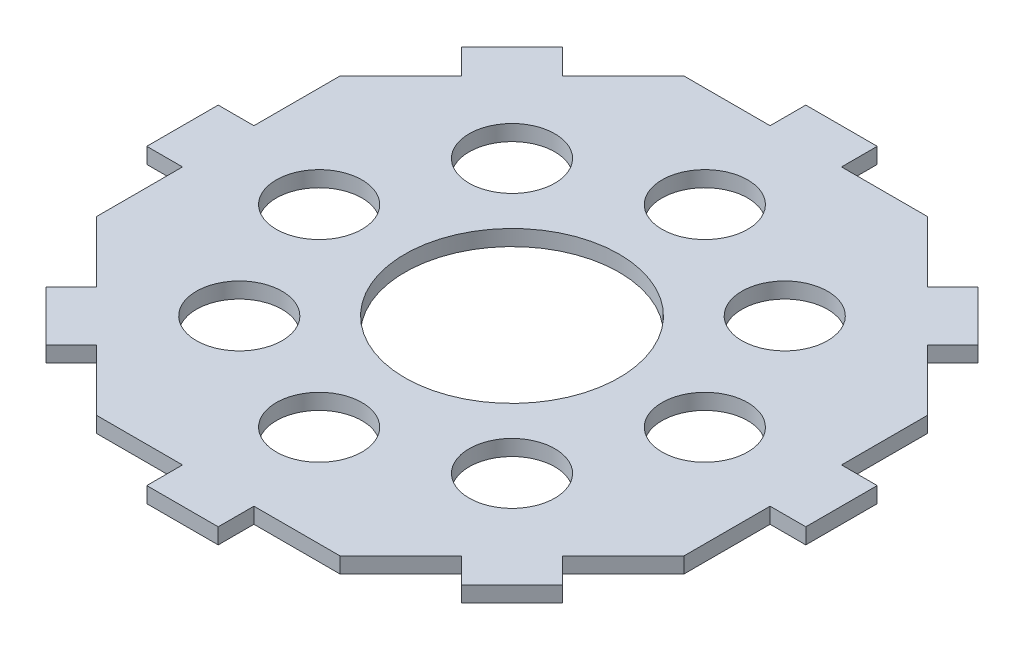
SolidWorks part; units mm, degrees
material "cardboard"
ref_plane "Front Plane" through (0, 0, 0) normal (0, 0, 1) x (1, 0, 0)
ref_plane "Top Plane" through (0, 0, 0) normal (0, 1, 0) x (1, 0, 0)
ref_plane "Right Plane" through (0, 0, 0) normal (1, 0, 0) x (0, 0, -1)
sketch "Sketch1" plane through (0, 0, 0) normal (0, 1, 0) x (1, 0, 0)
  line L0 (-132.1728, 127.1694) -> (-121.1728, 127.1694)
  line L1 (-122.1728, 123.1694) -> (-122.1728, 107.1694)
  line L2 (-62.3728, 123.1694) -> (-62.3728, 107.1694)
  line L3 (-119.7728, 107.1694) -> (-122.1728, 107.1694)
  line L4 (-133.5728, 123.1694) -> (-131.1728, 123.1694)
  line L5 (-133.5728, 123.1694) -> (-133.5728, 107.1694)
  line L6 (-133.5728, 107.1694) -> (-131.1728, 107.1694)
  line L7 (-131.1728, 123.1694) -> (-131.1728, 107.1694)
  line L8 (-119.7728, 123.1694) -> (-119.7728, 107.1694)
  line L9 (-119.7728, 123.1694) -> (-122.1728, 123.1694)
  line L10 (-59.9728, 123.1694) -> (-59.9728, 107.1694)
  line L11 (-96.5728, 127.1694) -> (-85.5728, 127.1694)
  line L12 (-62.3728, 123.1694) -> (-59.9728, 123.1694)
  line L13 (-62.3728, 107.1694) -> (-59.9728, 107.1694)
  line L14 (-50.9728, 123.1694) -> (-50.9728, 107.1694)
  line L15 (-48.5728, 123.1694) -> (-50.9728, 123.1694)
  line L16 (-48.5728, 123.1694) -> (-48.5728, 107.1694)
  line L17 (-48.5728, 107.1694) -> (-50.9728, 107.1694)
  line L18 (8.8272, 123.1694) -> (8.8272, 107.1694)
  line L19 (11.2272, 123.1694) -> (11.2272, 107.1694)
  line L20 (8.8272, 123.1694) -> (11.2272, 123.1694)
  line L21 (8.8272, 107.1694) -> (11.2272, 107.1694)
  line L22 (20.2272, 123.1694) -> (20.2272, 107.1694)
  line L23 (22.6272, 123.1694) -> (20.2272, 123.1694)
  line L24 (22.6272, 123.1694) -> (22.6272, 107.1694)
  line L25 (22.6272, 107.1694) -> (20.2272, 107.1694)
  line L26 (80.0272, 123.1694) -> (80.0272, 107.1694)
  line L27 (82.4272, 123.1694) -> (82.4272, 107.1694)
  line L28 (-60.9728, 127.1694) -> (-49.9728, 127.1694)
  line L29 (80.0272, 123.1694) -> (82.4272, 123.1694)
  line L30 (80.0272, 107.1694) -> (82.4272, 107.1694)
  line L31 (91.4272, 123.1694) -> (91.4272, 107.1694)
  line L32 (56.8272, 129.1694) -> (81.4272, 129.1694)
  line L33 (93.8272, 123.1694) -> (91.4272, 123.1694)
  line L34 (93.8272, 123.1694) -> (93.8272, 107.1694)
  line L35 (93.8272, 107.1694) -> (91.4272, 107.1694)
  line L36 (62.8843, 37.1328) -> (69.3002, 30.717)
  line L37 (82.7871, 17.2301) -> (84.767, 19.2099)
  line L38 (62.8843, 37.1328) -> (64.8642, 39.1127)
  line L39 (76.3712, 23.6459) -> (82.7871, 17.2301)
  line L40 (82.7871, -85.6209) -> (76.3712, -92.0368)
  line L41 (82.7871, -85.6209) -> (84.767, -87.6008)
  line L42 (84.767, -87.6008) -> (64.8642, -107.5036)
  line L43 (62.8843, -105.5237) -> (64.8642, -107.5036)
  line L44 (69.3002, -99.1078) -> (62.8843, -105.5237)
  line L45 (-39.9666, -105.5237) -> (-46.3825, -99.1078)
  line L46 (-39.9666, -105.5237) -> (-41.9465, -107.5036)
  line L47 (-41.9465, -107.5036) -> (-61.8493, -87.6008)
  line L48 (-59.8694, -85.6209) -> (-61.8493, -87.6008)
  line L49 (-53.4536, -92.0368) -> (-59.8694, -85.6209)
  line L50 (-25.3728, 127.1694) -> (-14.3728, 127.1694)
  line L51 (10.2272, 127.1694) -> (21.2272, 127.1694)
  line L52 (45.8272, 127.1694) -> (56.8272, 127.1694)
  line L53 (81.4272, 127.1694) -> (92.4272, 127.1694)
  line L54 (117.0272, 127.1694) -> (128.0272, 127.1694)
  line L55 (-36.6432, -102.2003) -> (-34.5738, -104.2697)
  line L56 (-6.2376, -76.0373) -> (-4.1682, -78.1068)
  line L57 (-56.546, -82.2975) -> (-58.3138, -84.0653)
  line L58 (-36.6432, -102.2003) -> (-38.411, -103.9681)
  line L59 (-32.4525, -49.8225) -> (-58.6154, -75.9854)
  line L60 (-58.6154, -80.2281) -> (-56.546, -82.2975)
  line L61 (-4.1682, -78.1068) -> (-30.3312, -104.2697)
  line L62 (-32.4525, -49.8225) -> (-30.3831, -51.8919)
  line L63 (-144.4728, 129.1694) -> (-132.1728, 129.1694)
  line L64 (-55.8571, 81.8711) -> (-55.8571, 86.8711)
  line L65 (-65.8571, 81.8711) -> (-65.8571, 86.8711)
  line L66 (-35.3072, 73.3591) -> (-31.7716, 76.8946)
  line L67 (-28.2361, 66.288) -> (-24.7006, 69.8235)
  line L68 (-19.724, 45.7381) -> (-14.724, 45.7381)
  line L69 (-19.724, 35.7381) -> (-14.724, 35.7381)
  line L70 (-28.2361, 15.1882) -> (-24.7006, 11.6526)
  line L71 (-35.3072, 8.1171) -> (-31.7716, 4.5816)
  line L72 (-55.8571, -0.3949) -> (-55.8571, -5.3949)
  line L73 (-65.8571, -0.3949) -> (-65.8571, -5.3949)
  line L74 (-86.407, 8.1171) -> (-89.9425, 4.5816)
  line L75 (61.3287, 35.5772) -> (67.7445, 29.1613)
  line L76 (74.8156, 22.0903) -> (81.2315, 15.6744)
  line L77 (74.8156, 22.0903) -> (76.3712, 23.6459)
  line L78 (67.7445, 29.1613) -> (69.3002, 30.717)
  line L79 (29.5322, -77.8285) -> (32.3607, -75)
  line L80 (55.0919, -16.122) -> (52.2634, -13.2936)
  line L81 (-144.4728, 129.1694) -> (-144.4728, 119.1694)
  line L82 (-6.6146, 9.4376) -> (-32.1742, -16.122)
  line L83 (-144.4728, 101.1694) -> (-128.6728, 101.1694)
  line L84 (-93.4781, 15.1882) -> (-97.0136, 11.6526)
  line L85 (-108.8728, 120.1694) -> (-108.8728, 110.1694)
  line L86 (64.8642, 39.1127) -> (84.767, 19.2099)
  line L87 (-22.9584, -48.7099) -> (-3.0557, -68.6127)
  line L88 (-22.9584, -48.7099) -> (-26.1404, -51.8919)
  line L89 (-3.0557, -68.6127) -> (-6.2376, -71.7947)
  line L90 (-32.1742, -16.122) -> (-67.1742, -16.122)
  line L91 (-82.1742, -31.122) -> (-82.1742, -37.2688)
  line L92 (-67.1742, -52.2688) -> (-34.8988, -52.2688)
  line L93 (-112.1728, 106.1694) -> (-114.6728, 106.1694)
  line L94 (-141.1728, 126.1694) -> (-138.6728, 126.1694)
  line L95 (-141.1728, 126.1694) -> (-141.1728, 106.1694)
  line L96 (-141.1728, 106.1694) -> (-138.6728, 106.1694)
  line L97 (-138.6728, 126.1694) -> (-138.6728, 106.1694)
  line L98 (-114.6728, 126.1694) -> (-114.6728, 106.1694)
  line L99 (29.5322, 9.4376) -> (29.5322, 44.4376)
  line L100 (14.5322, 59.4376) -> (8.3854, 59.4376)
  line L101 (-6.6146, 44.4376) -> (-6.6146, 9.4376)
  line L102 (-112.1728, 126.1694) -> (-114.6728, 126.1694)
  line L103 (-112.1728, 126.1694) -> (-112.1728, 106.1694)
  line L104 (-124.6728, 101.1694) -> (-110.3728, 101.1694)
  line L105 (-108.8728, 120.1694) -> (-108.8728, 110.1694)
  line L106 (55.0919, -52.2688) -> (90.0919, -52.2688)
  line L107 (105.0919, -37.2688) -> (105.0919, -31.122)
  line L108 (90.0919, -16.122) -> (55.0919, -16.122)
  line L109 (-74.7728, 101.1694) -> (-73.2728, 101.1694)
  line L110 (-73.2728, 129.1694) -> (-73.2728, 101.1694)
  line L111 (21.2272, 129.1694) -> (45.8272, 129.1694)
  line L112 (-73.2728, 129.1694) -> (-73.2728, 101.1694)
  line L113 (-73.2728, 101.1694) -> (-37.6728, 101.1694)
  line L114 (-37.6728, 129.1694) -> (-37.6728, 101.1694)
  line L115 (-6.6146, -80.5531) -> (-6.6146, -112.8285)
  line L116 (8.3854, -127.8285) -> (14.5322, -127.8285)
  line L117 (29.5322, -112.8285) -> (29.5322, -77.8285)
  line L118 (-14.3728, 129.1694) -> (10.2272, 129.1694)
  line L119 (-37.6728, 129.1694) -> (-37.6728, 101.1694)
  line L120 (-37.6728, 101.1694) -> (-2.0728, 101.1694)
  line L121 (-2.0728, 129.1694) -> (-2.0728, 101.1694)
  line L122 (-49.9728, 129.1694) -> (-25.3728, 129.1694)
  line L123 (-2.0728, 129.1694) -> (-2.0728, 101.1694)
  line L124 (52.2634, -55.0972) -> (55.0919, -52.2688)
  line L125 (25.9733, -68.6127) -> (45.8761, -48.7099)
  line L126 (81.2315, -84.0653) -> (74.8156, -90.4811)
  line L127 (45.8761, -48.7099) -> (81.2315, -84.0653)
  line L128 (74.8156, -90.4811) -> (76.3712, -92.0368)
  line L129 (78.3511, -94.0167) -> (71.2801, -101.0877)
  line L130 (25.9733, -68.6127) -> (61.3287, -103.9681)
  line L131 (67.7445, -97.5522) -> (69.3002, -99.1078)
  line L132 (67.7445, -97.5522) -> (61.3287, -103.9681)
  line L133 (-38.411, -103.9681) -> (-44.8269, -97.5522)
  line L134 (-44.8269, -97.5522) -> (-46.3825, -99.1078)
  line L135 (32.3607, 6.6092) -> (29.5322, 9.4376)
  line L136 (-101.9901, 35.7381) -> (-106.9901, 35.7381)
  line L137 (45.8761, -19.6809) -> (25.9733, 0.2219)
  line L138 (45.8761, -19.6809) -> (81.2315, 15.6744)
  line L139 (25.9733, 0.2219) -> (61.3287, 35.5772)
  line L140 (-48.3624, -101.0877) -> (-55.4335, -94.0167)
  line L141 (-51.8979, -90.4811) -> (-53.4536, -92.0368)
  line L142 (-51.8979, -90.4811) -> (-58.3138, -84.0653)
  line L143 (-65.8571, 81.8711) -> (-77.8949, 81.8711)
  line L144 (-77.8949, 81.8711) -> (-86.407, 73.3591)
  line L145 (-2.0728, 101.1694) -> (33.5272, 101.1694)
  line L146 (33.5272, 129.1694) -> (33.5272, 101.1694)
  line L147 (-85.5728, 129.1694) -> (-60.9728, 129.1694)
  line L148 (33.5272, 129.1694) -> (33.5272, 101.1694)
  line L149 (33.5272, 101.1694) -> (69.1272, 101.1694)
  line L150 (69.1272, 129.1694) -> (69.1272, 101.1694)
  line L151 (-121.1728, 129.1694) -> (-110.3728, 129.1694)
  line L152 (69.1272, 129.1694) -> (69.1272, 101.1694)
  line L153 (69.1272, 101.1694) -> (104.7272, 101.1694)
  line L154 (104.7272, 129.1694) -> (104.7272, 101.1694)
  line L155 (128.0272, 129.1694) -> (140.3272, 129.1694)
  line L156 (104.7272, 129.1694) -> (104.7272, 101.1694)
  line L157 (104.7272, 101.1694) -> (140.3272, 101.1694)
  line L158 (140.3272, 129.1694) -> (140.3272, 119.1694)
  line L159 (-69.9728, 126.1694) -> (-67.4728, 126.1694)
  line L160 (-69.9728, 126.1694) -> (-69.9728, 106.1694)
  line L161 (-69.9728, 106.1694) -> (-67.4728, 106.1694)
  line L162 (-67.4728, 126.1694) -> (-67.4728, 106.1694)
  line L163 (-43.4728, 126.1694) -> (-43.4728, 106.1694)
  line L164 (-40.9728, 106.1694) -> (-43.4728, 106.1694)
  line L165 (-40.9728, 126.1694) -> (-40.9728, 106.1694)
  line L166 (-40.9728, 126.1694) -> (-43.4728, 126.1694)
  line L167 (-61.4728, 101.1694) -> (-61.4728, 97.1694)
  line L168 (-61.4728, 97.1694) -> (-49.4728, 97.1694)
  line L169 (-49.4728, 97.1694) -> (-49.4728, 101.1694)
  line L170 (1.2272, 126.1694) -> (3.7272, 126.1694)
  line L171 (1.2272, 126.1694) -> (1.2272, 106.1694)
  line L172 (1.2272, 106.1694) -> (3.7272, 106.1694)
  line L173 (3.7272, 126.1694) -> (3.7272, 106.1694)
  line L174 (27.7272, 126.1694) -> (27.7272, 106.1694)
  line L175 (30.2272, 106.1694) -> (27.7272, 106.1694)
  line L176 (30.2272, 126.1694) -> (30.2272, 106.1694)
  line L177 (30.2272, 126.1694) -> (27.7272, 126.1694)
  line L178 (9.7272, 101.1694) -> (9.7272, 97.1694)
  line L179 (9.7272, 97.1694) -> (21.7272, 97.1694)
  line L180 (21.7272, 97.1694) -> (21.7272, 101.1694)
  line L181 (72.4272, 126.1694) -> (74.9272, 126.1694)
  line L182 (72.4272, 126.1694) -> (72.4272, 106.1694)
  line L183 (72.4272, 106.1694) -> (74.9272, 106.1694)
  line L184 (74.9272, 126.1694) -> (74.9272, 106.1694)
  line L185 (98.9272, 126.1694) -> (98.9272, 106.1694)
  line L186 (101.4272, 106.1694) -> (98.9272, 106.1694)
  line L187 (101.4272, 126.1694) -> (101.4272, 106.1694)
  line L188 (101.4272, 126.1694) -> (98.9272, 126.1694)
  line L189 (80.9272, 101.1694) -> (80.9272, 97.1694)
  line L190 (80.9272, 97.1694) -> (92.9272, 97.1694)
  line L191 (92.9272, 97.1694) -> (92.9272, 101.1694)
  line L192 (-128.6728, 101.1694) -> (-128.6728, 102.1694)
  line L193 (-128.6728, 102.1694) -> (-124.6728, 102.1694)
  line L194 (-124.6728, 102.1694) -> (-124.6728, 101.1694)
  line L195 (-61.4728, 100.1694) -> (-57.4728, 100.1694)
  line L196 (-57.4728, 100.1694) -> (-57.4728, 102.1694)
  line L197 (-57.4728, 102.1694) -> (-53.4728, 102.1694)
  line L198 (-53.4728, 102.1694) -> (-53.4728, 100.1694)
  line L199 (-53.4728, 100.1694) -> (-49.4728, 100.1694)
  line L200 (9.7272, 100.1694) -> (13.7272, 100.1694)
  line L201 (13.7272, 100.1694) -> (13.7272, 102.1694)
  line L202 (13.7272, 102.1694) -> (17.7272, 102.1694)
  line L203 (27.3876, 1.6361) -> (33.7515, -4.7279)
  line L204 (33.7515, -4.7279) -> (30.9231, -7.5563)
  line L205 (30.9231, -7.5563) -> (38.098, -14.7312)
  line L206 (38.098, -14.7312) -> (40.9264, -11.9027)
  line L207 (40.9264, -11.9027) -> (47.2903, -18.2667)
  line L208 (47.2903, -50.1241) -> (40.9264, -56.4881)
  line L209 (40.9264, -56.4881) -> (38.098, -53.6597)
  line L210 (38.098, -53.6597) -> (30.9231, -60.8345)
  line L211 (30.9231, -60.8345) -> (33.7515, -63.663)
  line L212 (33.7515, -63.663) -> (27.3876, -70.0269)
  line L213 (-4.4699, -70.0269) -> (-10.8338, -63.663)
  line L214 (-10.8338, -63.663) -> (-8.0054, -60.8345)
  line L215 (-8.0054, -60.8345) -> (-15.1803, -53.6597)
  line L216 (-15.1803, -53.6597) -> (-18.0087, -56.4881)
  line L217 (-18.0087, -56.4881) -> (-24.3727, -50.1241)
  line L218 (-89.9425, 76.8946) -> (-97.0136, 69.8235)
  line L219 (-93.4781, 66.288) -> (-101.9901, 57.7759)
  line L220 (-101.9901, 57.7759) -> (-101.9901, 45.7381)
  line L221 (-106.9901, 45.7381) -> (-106.9901, 35.7381)
  line L222 (-101.9901, 35.7381) -> (-101.9901, 23.7002)
  line L223 (-101.9901, 23.7002) -> (-93.4781, 15.1882)
  line L224 (-97.0136, 11.6526) -> (-89.9425, 4.5816)
  line L225 (-86.407, 8.1171) -> (-77.8949, -0.3949)
  line L226 (-77.8949, -0.3949) -> (-65.8571, -0.3949)
  line L227 (-65.8571, -5.3949) -> (-55.8571, -5.3949)
  line L228 (-55.8571, -0.3949) -> (-43.8192, -0.3949)
  line L229 (-43.8192, -0.3949) -> (-35.3072, 8.1171)
  line L230 (-31.7716, 4.5816) -> (-24.7006, 11.6526)
  line L231 (-28.2361, 15.1882) -> (-19.724, 23.7002)
  line L232 (-19.724, 23.7002) -> (-19.724, 35.7381)
  line L233 (-14.724, 35.7381) -> (-14.724, 45.7381)
  line L234 (-19.724, 45.7381) -> (-19.724, 57.7759)
  line L235 (-19.724, 57.7759) -> (-28.2361, 66.288)
  line L236 (-24.7006, 69.8235) -> (-31.7716, 76.8946)
  line L237 (-35.3072, 73.3591) -> (-43.8192, 81.8711)
  line L238 (-43.8192, 81.8711) -> (-55.8571, 81.8711)
  line L239 (-55.8571, 86.8711) -> (-65.8571, 86.8711)
  line L240 (-101.9901, 45.7381) -> (-106.9901, 45.7381)
  line L241 (-93.4781, 66.288) -> (-97.0136, 69.8235)
  line L242 (-86.407, 73.3591) -> (-89.9425, 76.8946)
  line L243 (17.7272, 102.1694) -> (17.7272, 100.1694)
  line L244 (17.7272, 100.1694) -> (21.7272, 100.1694)
  line L245 (80.9272, 100.1694) -> (84.9272, 100.1694)
  line L246 (84.9272, 100.1694) -> (84.9272, 102.1694)
  line L247 (84.9272, 102.1694) -> (88.9272, 102.1694)
  line L248 (88.9272, 102.1694) -> (88.9272, 100.1694)
  line L249 (88.9272, 100.1694) -> (92.9272, 100.1694)
  line L250 (140.3272, 119.1694) -> (142.3272, 119.1694)
  line L251 (142.3272, 111.1694) -> (140.3272, 111.1694)
  line L252 (140.3272, 111.1694) -> (140.3272, 101.1694)
  line L253 (-144.4728, 119.1694) -> (-143.4728, 119.1694)
  line L254 (-143.4728, 119.1694) -> (-143.4728, 111.1694)
  line L255 (-143.4728, 111.1694) -> (-144.4728, 111.1694)
  line L256 (-144.4728, 111.1694) -> (-144.4728, 101.1694)
  line L257 (-110.3728, 129.1694) -> (-110.3728, 120.1694)
  line L258 (-110.3728, 120.1694) -> (-108.8728, 120.1694)
  line L259 (-108.8728, 110.1694) -> (-110.3728, 110.1694)
  line L260 (-110.3728, 110.1694) -> (-110.3728, 101.1694)
  line L261 (-74.7728, 129.1694) -> (-74.7728, 120.1694)
  line L262 (-74.7728, 120.1694) -> (-71.7728, 120.1694)
  line L263 (-71.7728, 120.1694) -> (-71.7728, 110.1694)
  line L264 (-71.7728, 110.1694) -> (-74.7728, 110.1694)
  line L265 (-74.7728, 110.1694) -> (-74.7728, 101.1694)
  line L266 (-39.1728, 129.1694) -> (-39.1728, 120.1694)
  line L267 (-39.1728, 120.1694) -> (-36.1728, 120.1694)
  line L268 (-36.1728, 120.1694) -> (-36.1728, 110.1694)
  line L269 (-36.1728, 110.1694) -> (-39.1728, 110.1694)
  line L270 (-39.1728, 110.1694) -> (-39.1728, 101.1694)
  line L271 (-3.5728, 129.1694) -> (-3.5728, 120.1694)
  line L272 (-3.5728, 120.1694) -> (-0.5728, 120.1694)
  line L273 (-0.5728, 120.1694) -> (-0.5728, 110.1694)
  line L274 (-0.5728, 110.1694) -> (-3.5728, 110.1694)
  line L275 (-3.5728, 110.1694) -> (-3.5728, 101.1694)
  line L276 (32.0272, 129.1694) -> (32.0272, 120.1694)
  line L277 (32.0272, 120.1694) -> (35.0272, 120.1694)
  line L278 (35.0272, 120.1694) -> (35.0272, 110.1694)
  line L279 (35.0272, 110.1694) -> (32.0272, 110.1694)
  line L280 (32.0272, 110.1694) -> (32.0272, 101.1694)
  line L281 (67.6272, 129.1694) -> (67.6272, 120.1694)
  line L282 (67.6272, 120.1694) -> (70.6272, 120.1694)
  line L283 (70.6272, 120.1694) -> (70.6272, 110.1694)
  line L284 (70.6272, 110.1694) -> (67.6272, 110.1694)
  line L285 (67.6272, 110.1694) -> (67.6272, 101.1694)
  line L286 (103.2272, 129.1694) -> (103.2272, 120.1694)
  line L287 (103.2272, 120.1694) -> (106.2272, 120.1694)
  line L288 (106.2272, 120.1694) -> (106.2272, 110.1694)
  line L289 (106.2272, 110.1694) -> (103.2272, 110.1694)
  line L290 (103.2272, 110.1694) -> (103.2272, 101.1694)
  line L291 (142.3272, 119.1694) -> (142.3272, 111.1694)
  line L292 (-132.1728, 129.1694) -> (-132.1728, 127.1694)
  line L293 (-121.1728, 129.1694) -> (-121.1728, 127.1694)
  line L294 (-96.5728, 129.1694) -> (-96.5728, 127.1694)
  line L295 (-85.5728, 129.1694) -> (-85.5728, 127.1694)
  line L296 (-60.9728, 129.1694) -> (-60.9728, 127.1694)
  line L297 (-49.9728, 129.1694) -> (-49.9728, 127.1694)
  line L298 (-25.3728, 129.1694) -> (-25.3728, 127.1694)
  line L299 (-14.3728, 129.1694) -> (-14.3728, 127.1694)
  line L300 (10.2272, 129.1694) -> (10.2272, 127.1694)
  line L301 (21.2272, 129.1694) -> (21.2272, 127.1694)
  line L302 (45.8272, 129.1694) -> (45.8272, 127.1694)
  line L303 (56.8272, 129.1694) -> (56.8272, 127.1694)
  line L304 (81.4272, 129.1694) -> (81.4272, 127.1694)
  line L305 (92.4272, 129.1694) -> (92.4272, 127.1694)
  line L306 (117.0272, 129.1694) -> (117.0272, 127.1694)
  line L307 (128.0272, 129.1694) -> (128.0272, 127.1694)
  line L308 (92.4272, 129.1694) -> (117.0272, 129.1694)
  circle A0 centre (-32.4525, -56.8936) radius 1.75
  circle A1 centre (-60.8571, 67.7381) radius 6
  circle A2 centre (-41.7652, 59.83) radius 6
  circle A3 centre (-33.8571, 40.7381) radius 6
  circle A4 centre (-11.2393, -78.1068) radius 1.75
  circle A5 centre (-32.4525, -99.32) radius 1.75
  circle A6 centre (11.4588, 34.4376) radius 10
  circle A7 centre (-126.6728, 113.6694) radius 1
  circle A8 centre (-53.6657, -78.1068) radius 1.75
  arc A9 (-30.3831, -51.8919) -> (-26.1404, -51.8919) centre (-28.2617, -49.7706) ccw
  arc A10 (-6.2376, -76.0373) -> (-6.2376, -71.7947) centre (-4.1163, -73.916) cw
  circle A11 centre (-55.4728, 113.6694) radius 1
  circle A12 centre (80.0919, -34.1954) radius 10
  circle A13 centre (11.4588, -34.1954) radius 15
  arc A14 (-67.1742, -16.122) -> (-82.1742, -31.122) centre (-67.1742, -31.122) ccw
  arc A15 (-82.1742, -37.2688) -> (-67.1742, -52.2688) centre (-67.1742, -37.2688) ccw
  arc A16 (-6.6146, -112.8285) -> (8.3854, -127.8285) centre (8.3854, -112.8285) ccw
  arc A17 (14.5322, -127.8285) -> (29.5322, -112.8285) centre (14.5322, -112.8285) ccw
  arc A18 (90.0919, -52.2688) -> (105.0919, -37.2688) centre (90.0919, -37.2688) ccw
  arc A19 (105.0919, -31.122) -> (90.0919, -16.122) centre (90.0919, -31.122) ccw
  arc A20 (29.5322, 44.4376) -> (14.5322, 59.4376) centre (14.5322, 44.4376) ccw
  circle A21 centre (15.7272, 113.6694) radius 1
  circle A22 centre (11.4588, -102.8285) radius 10
  circle A23 centre (86.9272, 113.6694) radius 1
  circle A24 centre (-57.1742, -34.1954) radius 10
  circle A25 centre (-41.7652, 21.6462) radius 6
  circle A26 centre (-91.0728, 115.1694) radius 7.5
  circle A27 centre (-19.8728, 115.1694) radius 7.5
  circle A28 centre (51.3272, 115.1694) radius 7.5
  circle A29 centre (122.5272, 115.1694) radius 7.5
  arc A30 (8.3854, 59.4376) -> (-6.6146, 44.4376) centre (8.3854, 44.4376) ccw
  arc A31 (-34.5738, -104.2697) -> (-30.3312, -104.2697) centre (-32.4525, -102.1484) ccw
  arc A32 (-58.6154, -75.9854) -> (-58.6154, -80.2281) centre (-56.4941, -78.1068) ccw
  circle A33 centre (-60.8571, 13.7381) radius 6
  circle A34 centre (-79.949, 21.6462) radius 6
  circle A35 centre (-87.8571, 40.7381) radius 6
  circle A36 centre (-79.949, 59.83) radius 6
  circle A37 centre (-60.8571, 40.7381) radius 15
  point P67 (11.4588, -34.1954)
  point P113 (11.4588, -34.1954)
  point P166 (11.4588, -34.1954)
  point P168 (11.4588, -34.1954)
  point P177 (11.4588, -34.1954)
  point P182 (11.4588, -34.1954)
  point P246 (11.4588, -34.1954)
  point P268 (11.4588, -34.1954)
  point P279 (11.4588, -34.1954)
  point P313 (-60.8571, 40.7381)
  point P314 (-60.8571, 40.7381)
  point P399 (-60.8571, 40.7381)
extrude "Boss-Extrude1" add sketch "Sketch1" along normal blind 2.2 contours L144 L242 L218 L241 L219 L220 L240 L221 L136 L222 L223 L84 L224 L74 L225 L226 L73 L227 L72 L228 L229 L71 L230 L70 L231 L232 L69 L233 L68 L234 L235 L67 L236 L66 L237 L238 L64 L239 L65 L143 A37 A36 A35 A34 A33
